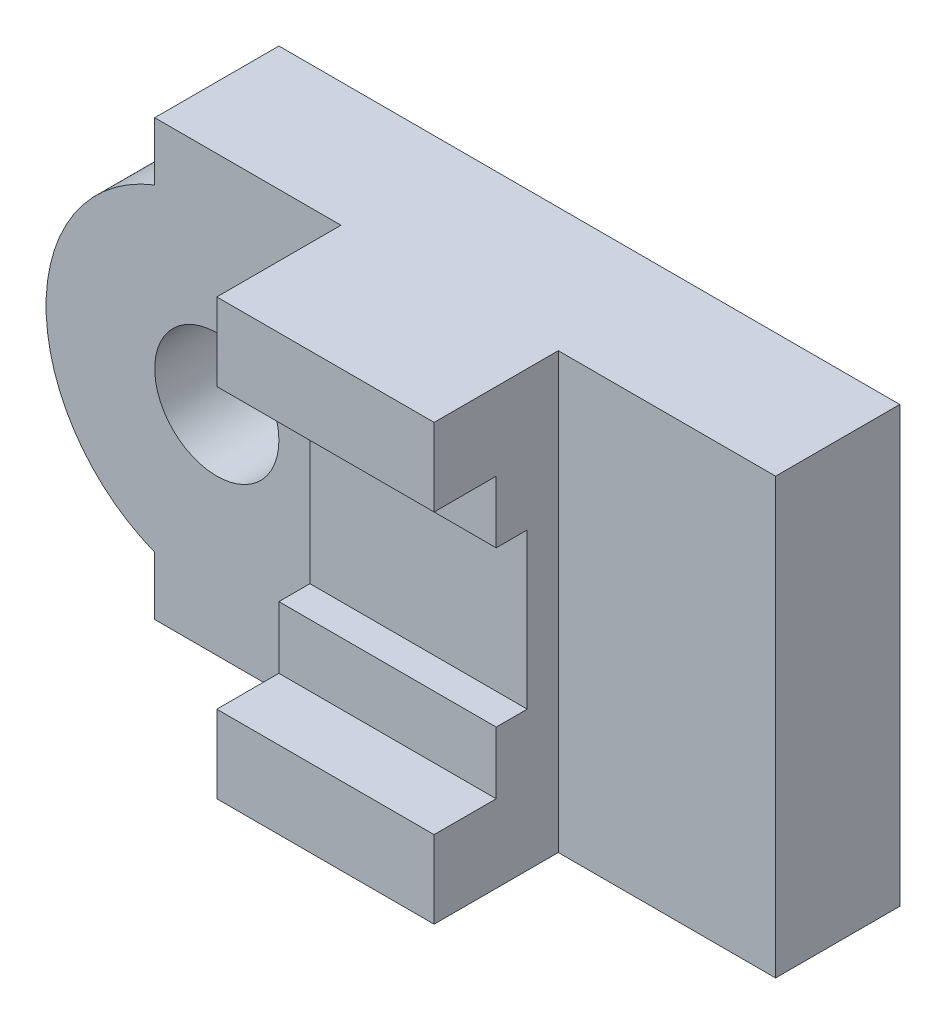
SolidWorks part; units mm, degrees
ref_plane "Спереди" through (0, 0, 0) normal (0, 0, 1) x (1, 0, 0)
ref_plane "Сверху" through (0, 0, 0) normal (0, 1, 0) x (1, 0, 0)
ref_plane "Справа" through (0, 0, 0) normal (1, 0, 0) x (0, 0, -1)
sketch "Эскиз1" plane through (0, 0, 0) normal (0, 0, 1) x (1, 0, 0)
  line L1 (-50, -35) -> (50, -35)
  line L2 (-50, -35) -> (-50, 35)
  line L3 (-50, 35) -> (50, 35)
  line L4 (50, -35) -> (50, 35)
  line L5 (-50, -35) -> (50, 35) construction
  line L6 (-50, 35) -> (50, -35) construction
  circle A0 centre (-40, 0) radius 27.5
  circle A1 centre (-40, 0) radius 10
  point P0 (0, 0)
  dimension "D3" = 55
  dimension "D5" = 20
  dimension "D1" = 100
  dimension "D2" = 70
  dimension "D4" = 40
extrude "Бобышка-Вытянуть1" add sketch "Эскиз1" along normal blind 20 contours L2 A0 | L2 A0 | A0 L2 L1 L4 L3
ref_plane "Плоскость1" through (-20, 0, 0) normal (-1, 0, 0) x (0, 0, 1)
sketch "Эскиз2" plane through (-20, 0, 0) normal (-1, 0, 0) x (0, 0, 1)
  line L1 (0, -35) -> (40, -35)
  line L2 (0, -35) -> (0, 35)
  line L3 (0, 35) -> (40, 35)
  line L4 (40, -35) -> (40, 35)
  line L5 (30, -22.5) -> (40, -22.5)
  line L6 (30, -22.5) -> (30, 22.5)
  line L7 (30, 22.5) -> (40, 22.5)
  line L8 (40, -22.5) -> (40, 22.5)
  line L9 (30, -22.5) -> (40, 22.5) construction
  line L10 (30, 22.5) -> (40, -22.5) construction
  line L11 (25, -12.5) -> (30, -12.5)
  line L12 (25, -12.5) -> (25, 12.5)
  line L13 (25, 12.5) -> (30, 12.5)
  line L14 (30, -12.5) -> (30, 12.5)
  line L15 (25, -12.5) -> (30, 12.5) construction
  line L16 (25, 12.5) -> (30, -12.5) construction
  point P5 (35, 0)
  point P11 (27.5, 0)
  dimension "D1" = 40
  dimension "D2" = 45
  dimension "D3" = 10
  dimension "D4" = 5
  dimension "D5" = 25
extrude "Бобышка-Вытянуть2" add sketch "Эскиз2" against normal blind 35 contours L12 L13 L6 L7 L4 L3 L2 L1 L5 L11
